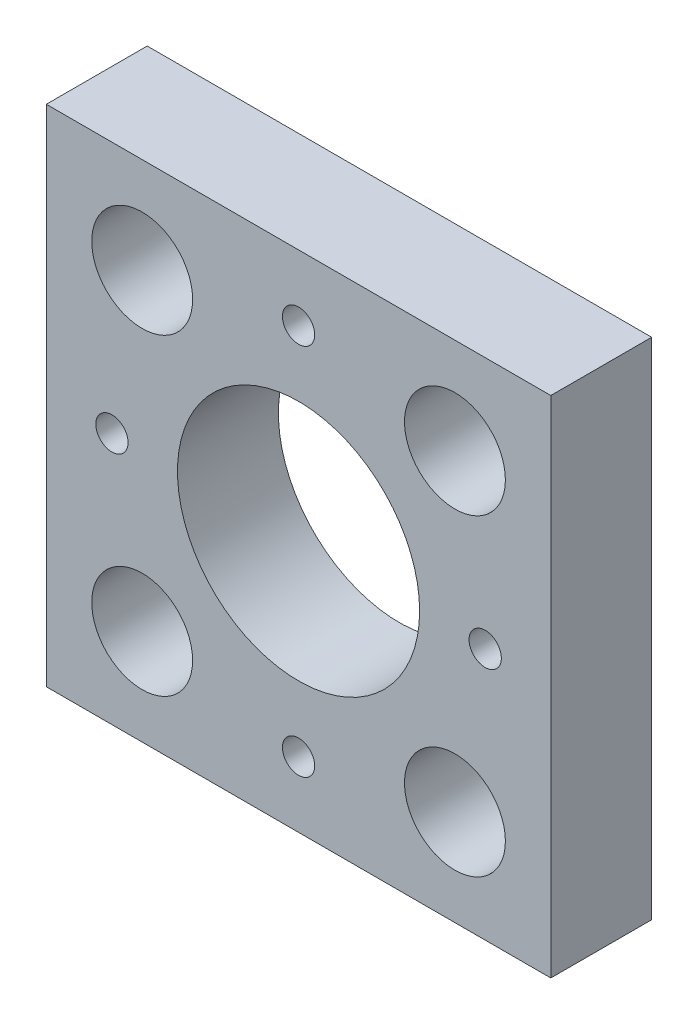
SolidWorks part; units mm, degrees
ref_plane "前视基准面" through (0, 0, 0) normal (0, 0, 1) x (1, 0, 0)
ref_plane "上视基准面" through (0, 0, 0) normal (0, 1, 0) x (1, 0, 0)
ref_plane "右视基准面" through (0, 0, 0) normal (1, 0, 0) x (0, 0, -1)
other "Configuration Table"
sketch "草图1" plane through (0, 0, 0) normal (0, 0, 1) x (1, 0, 0)
  line L1 (-25, -25) -> (25, -25)
  line L2 (-25, -25) -> (-25, 25)
  line L3 (-25, 25) -> (25, 25)
  line L4 (25, -25) -> (25, 25)
  line L5 (-25, -25) -> (25, 25) construction
  line L6 (-25, 25) -> (25, -25) construction
  point P0 (0, 0)
  dimension "D1" = 50
  dimension "D2" = 50
extrude "凸台-拉伸1" add sketch "草图1" along normal blind 10
hole_wizard "中间大孔" positions "草图2" profile "草图3" legacy end condition through all
sketch "草图2" plane through (0, 0, 10) normal (0, 0, 1) x (1, 0, 0)
  point P0 (0, 0)
sketch "草图3" plane through (0, 0, 10) normal (1, 0, 0) x (0, -1, 0)
  line L0 (0, 0) -> (0, 10)
  line L1 (0, 10) -> (12, 10)
  line L2 (12, 10) -> (12, 0)
  line L3 (12, 0) -> (0, 0)
  line L4 (0, 110) -> (0, -10) construction
  dimension "直径" = 24
  dimension "深度" = 10
sketch "草图6" plane through (0, 0, 10) normal (0, 0, 1) x (1, 0, 0)
  line L0 (0, 0) -> (25, 0) construction
  line L2 (0, 0) -> (0, 25) construction
sketch "草图7" plane through (0, 0, 10) normal (0, 0, 1) x (1, 0, 0)
  line L1 (-15.5, -15.5) -> (15.5, -15.5)
  line L2 (-15.5, -15.5) -> (-15.5, 15.5)
  line L3 (-15.5, 15.5) -> (15.5, 15.5)
  line L4 (15.5, -15.5) -> (15.5, 15.5)
  line L5 (-15.5, -15.5) -> (15.5, 15.5) construction
  line L6 (-15.5, 15.5) -> (15.5, -15.5) construction
  circle A0 centre (0, 0) radius 18.5
  point P0 (0, 0)
  dimension "D3" = 21.9203
  dimension "D4" = 37
  dimension "D1" = 31
  dimension "D2" = 31
hole_wizard "孔2" positions "草图11" profile "草图12" legacy end condition through all
sketch "草图11" plane through (0, 0, 10) normal (0, 0, 1) x (1, 0, 0)
  line L0 (0, -200000) -> (0, 200025) construction
  line L1 (-200000, 0) -> (200025, 0) construction
  circle A0 centre (0, 0) radius 18.5 construction
  point P0 (0, 18.5)
  point P6 (18.5, 0)
  point P10 (0, -18.5)
  point P12 (-18.5, 0)
sketch "草图12" plane through (0, 18.5, 10) normal (1, 0, 0) x (0, -1, 0)
  line L0 (0, 0) -> (0, 10)
  line L1 (0, 10) -> (1.6, 10)
  line L2 (1.6, 10) -> (1.6, 0)
  line L3 (1.6, 0) -> (0, 0)
  line L4 (0, 110) -> (0, -10) construction
  dimension "直径" = 3.2
  dimension "深度" = 10
hole_wizard "孔3" positions "草图15" profile "草图14" legacy end condition through all
sketch "草图15" plane through (0, 0, 10) normal (0, 0, 1) x (1, 0, 0)
  point P0 (-15.5, 15.5)
  point P3 (15.5, 15.5)
  point P6 (15.5, -15.5)
  point P9 (-15.5, -15.5)
sketch "草图14" plane through (-15.5, 15.5, 10) normal (1, 0, 0) x (0, -1, 0)
  line L0 (0, 0) -> (0, 10)
  line L1 (0, 10) -> (5, 10)
  line L2 (5, 10) -> (5, 0)
  line L3 (5, 0) -> (0, 0)
  line L4 (0, 110) -> (0, -10) construction
  dimension "直径" = 10
  dimension "深度" = 10
